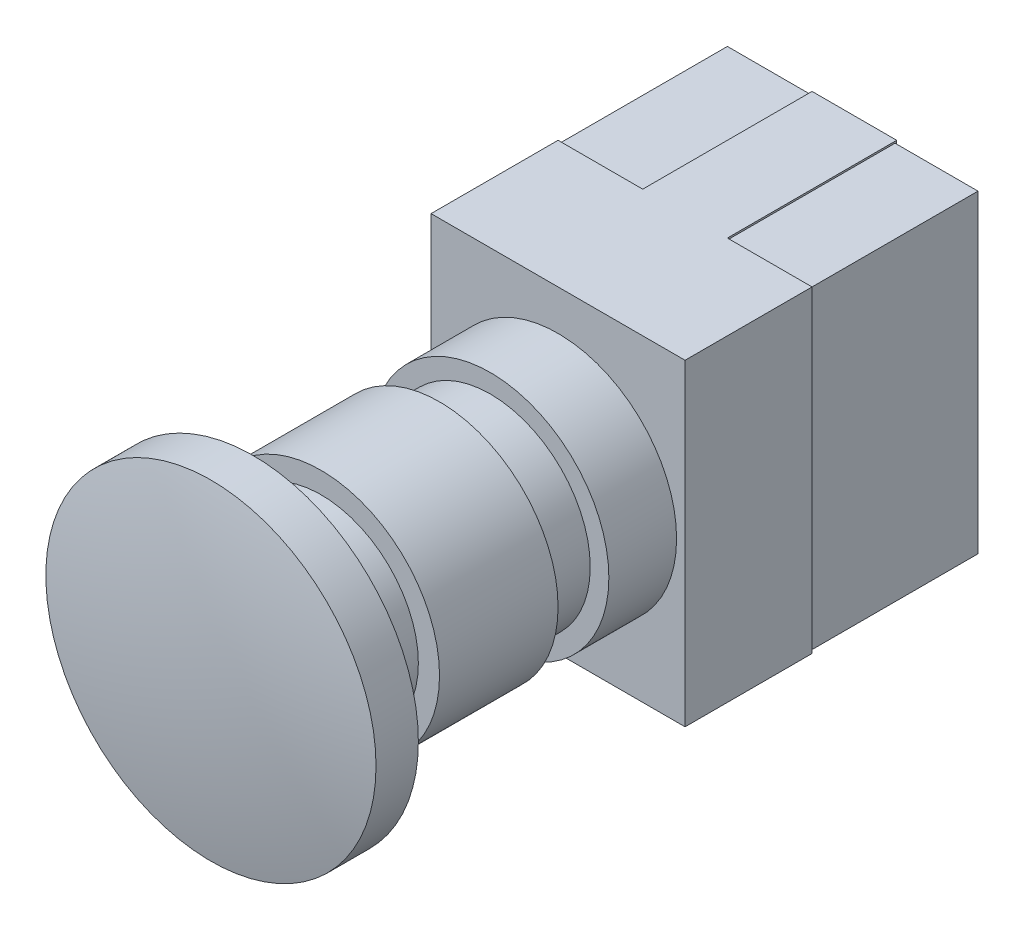
SolidWorks part; units mm, degrees
ref_plane "Plan de face" through (0, 0, 0) normal (0, 0, 1) x (1, 0, 0)
ref_plane "Plan de dessus" through (0, 0, 0) normal (0, 1, 0) x (1, 0, 0)
ref_plane "Plan de droite" through (0, 0, 0) normal (1, 0, 0) x (0, 0, -1)
sketch "Esquisse1" plane through (0, 0, 0) normal (0, 0, 1) x (1, 0, 0)
  line L1 (-15, 18.75) -> (15, 18.75)
  line L2 (-15, 18.75) -> (-15, -18.75)
  line L3 (-15, -18.75) -> (15, -18.75)
  line L4 (15, 18.75) -> (15, -18.75)
  line L5 (-15, 18.75) -> (15, -18.75) construction
  line L6 (-15, -18.75) -> (15, 18.75) construction
  point P0 (0, 0)
  dimension "D1" = 37.5
  dimension "D2" = 30
extrude "Boss.-Extru.1" add sketch "Esquisse1" along normal blind 35
sketch "Esquisse2" plane through (0, 0, 35) normal (0, 0, 1) x (1, 0, 0)
  circle A0 centre (0, 0) radius 14
  dimension "D1" = 28
extrude "Boss.-Extru.2" add sketch "Esquisse2" along normal blind 8
sketch "Esquisse3" plane through (0, 0, 43) normal (0, 0, 1) x (1, 0, 0)
  circle A0 centre (0, 0) radius 11.8
  dimension "D1" = 23.6
extrude "Boss.-Extru.3" add sketch "Esquisse3" along normal blind 6
sketch "Esquisse4" plane through (0, 0, 49) normal (0, 0, 1) x (1, 0, 0)
  circle A0 centre (0, 0) radius 14
extrude "Boss.-Extru.4" add sketch "Esquisse4" along normal blind 14
sketch "Esquisse5" plane through (0, 0, 63) normal (0, 0, 1) x (1, 0, 0)
  circle A0 centre (0, 0) radius 11.5
  dimension "D1" = 23
extrude "Boss.-Extru.5" add sketch "Esquisse5" along normal blind 8
sketch "Esquisse7" plane through (0, 0, 0) normal (0, 1, 0) x (1, 0, 0)
  line L0 (0, -71) -> (12.5, -71)
  line L1 (-11.5, -71) -> (11.5, -71) construction
  line L2 (19.5, -71) -> (19.5, -76)
  line L3 (0, -78) -> (0, -71)
  line L4 (11.5, -71) -> (11.5, -63) construction
  line L6 (18.5, -71) -> (18.5, -72)
  line L7 (18.5, -72) -> (12.5, -72)
  line L8 (12.5, -71) -> (12.5, -72)
  line L9 (18.5, -71) -> (19.5, -71)
  arc A0 (19.5, -76) -> (0, -78) centre (0, 18.0625) cw
  dimension "D3" = 7
  dimension "D1" = 19.5
  dimension "D2" = 5
  dimension "D4" = 1
  dimension "D5" = 1
  dimension "D6" = 1
ref_axis "Axe1" through (0, 0, 71) along (0, 0, -1)
revolve "Révolution1" add sketch "Esquisse7" angle 360 about axis through (0, 0, 71) along (0, 0, -1)
sketch "Esquisse8" plane through (0, 0, 0) normal (0, 0, -1) x (-1, 0, 0)
  line L0 (-5, 18.75) -> (-5, 18.55)
  line L1 (14.8, -18.55) -> (5, -18.55)
  line L2 (14.8, -18.55) -> (14.8, 18.55)
  line L3 (14.8, 18.55) -> (5, 18.55)
  line L4 (-14.8, -18.55) -> (-14.8, 18.55)
  line L5 (14.8, -18.55) -> (-14.8, 18.55) construction
  line L6 (14.8, 18.55) -> (-14.8, -18.55) construction
  line L7 (15, -18.75) -> (5, -18.75)
  line L8 (15, -18.75) -> (15, 18.75)
  line L9 (15, 18.75) -> (5, 18.75)
  line L10 (-15, -18.75) -> (-15, 18.75)
  line L11 (15, -18.75) -> (-15, 18.75) construction
  line L12 (15, 18.75) -> (-15, -18.75) construction
  line L13 (5, -18.75) -> (5, -18.55)
  line L16 (-5, -18.55) -> (-5, -18.75)
  line L17 (-5, 18.75) -> (-15, 18.75)
  line L18 (-5, 18.55) -> (-14.8, 18.55)
  line L19 (5, 18.55) -> (5, 18.75)
  line L22 (-5, -18.55) -> (-14.8, -18.55)
  line L23 (-5, -18.75) -> (-15, -18.75)
  point P0 (0, 0)
  point P5 (0, 0)
  dimension "D1" = 0.2
  dimension "D2" = 0.2
  dimension "D3" = 10
  dimension "D4" = 10
extrude "Enlèv. mat.-Extru.1" cut sketch "Esquisse8" against normal blind 20
sketch "Esquisse9" plane through (0, 0, 0) normal (0, 0, -1) x (-1, 0, 0)
  line L1 (-14.8, 18.55) -> (-5, 18.55)
  line L2 (-14.8, 18.55) -> (-14.8, -18.55)
  line L3 (-14.8, -18.55) -> (-5, -18.55)
  line L4 (-5, 18.55) -> (-5, -18.55)
  line L5 (5, -18.55) -> (14.8, -18.55)
  line L6 (5, -18.55) -> (5, 18.55)
  line L7 (5, 18.55) -> (14.8, 18.55)
  line L8 (14.8, -18.55) -> (14.8, 18.55)
extrude "Enlèv. mat.-Extru.2" cut sketch "Esquisse9" against normal blind 0.2
